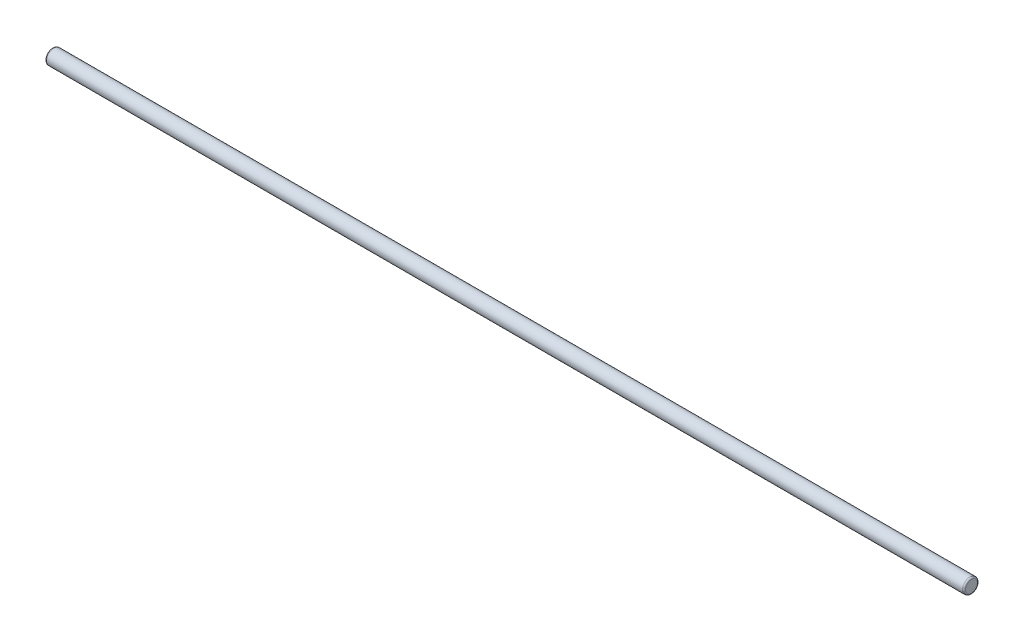
SolidWorks part; units mm, degrees
ref_plane "Front Plane" through (0, 0, 0) normal (1, 0, 0) x (0, 1, 0)
ref_plane "Top Plane" through (0, 0, 0) normal (0, 0, 1) x (0, 1, 0)
ref_plane "Right Plane" through (0, 0, 0) normal (0, 1, 0) x (-1, 0, 0)
sketch "Sketch1" plane through (0, 0, 0) normal (1, 0, 0) x (0, 1, 0)
  circle A0 centre (0, 0) radius 5
  dimension "D1" = 10
extrude "Boss-Extrude1" add sketch "Sketch1" along normal mid plane 620
fillet "Fillet2" radius 1 2 edges at (-310, 0, -5) (310, 0, -5)
